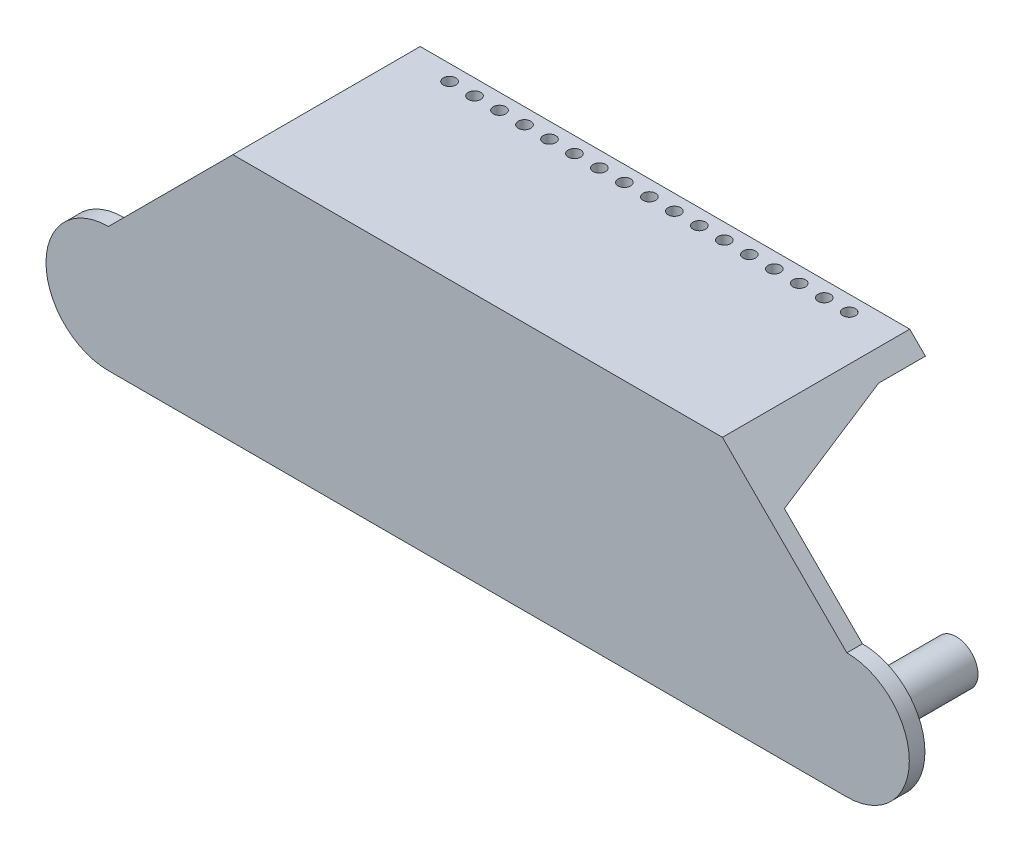
SolidWorks part; units mm, degrees
ref_plane "Спереди" through (0, 0, 0) normal (0, 0, 1) x (1, 0, 0)
ref_plane "Сверху" through (0, 0, 0) normal (0, 1, 0) x (1, 0, 0)
ref_plane "Справа" through (0, 0, 0) normal (1, 0, 0) x (0, 0, -1)
other "Configuration Table"
sketch "Эскиз1" plane through (0, 0, 0) normal (0, 0, 1) x (1, 0, 0)
  line L0 (-118.25, 0) -> (118.25, 0) construction
  line L1 (-118.25, -20) -> (118.25, -20)
  line L3 (-118.25, 20) -> (118.25, 20)
  line L5 (-118.25, -20) -> (118.25, 20) construction
  line L6 (-118.25, 20) -> (118.25, -20) construction
  arc A0 (-118.25, 20) -> (-118.25, -20) centre (-118.25, 0) ccw
  arc A1 (118.25, -20) -> (118.25, 20) centre (118.25, 0) ccw
  point P0 (0, 0)
  dimension "D3" = 20
  dimension "D1" = 236.5
  dimension "D2" = 40
extrude "Бобышка-Вытянуть1" add sketch "Эскиз1" along normal blind 5
sketch "Эскиз2" plane through (0, 0, 0) normal (0, 0, -1) x (-1, 0, 0)
  line L0 (-138.25, 0) -> (138.25, 0) construction
  line L1 (-118.25, 20) -> (-118.25, -20) construction
  line L2 (118.25, -20) -> (-118.25, -20) construction
  line L3 (118.25, 20) -> (118.25, -20) construction
  arc A0 (-118.25, 20) -> (-118.25, -20) centre (-118.25, 0) ccw construction
  arc A1 (118.25, -20) -> (118.25, 20) centre (118.25, 0) ccw construction
  circle A2 centre (-118.25, 0) radius 7
  circle A3 centre (118.25, 0) radius 7
  dimension "D1" = 14
extrude "Бобышка-Вытянуть2" add sketch "Эскиз2" along normal blind 30
sketch "Эскиз3" plane through (0, 0, 5) normal (0, 0, 1) x (1, 0, 0)
  line L0 (-138.25, 0) -> (138.25, 0) construction
  line L1 (-118.25, 20) -> (-118.25, -20) construction
  line L2 (118.25, 20) -> (118.25, -20) construction
  line L3 (-118.25, 20) -> (-78.4, 59.85)
  line L6 (78.4, 59.85) -> (-78.4, 59.85)
  line L8 (118.5, 0) -> (-118.25, 60.1) construction
  line L9 (118.25, 60.1) -> (-118.5, 0.0005) construction
  line L10 (118.25, 20) -> (-118.25, 20) construction
  line L11 (118.25, 20) -> (78.4, 59.85)
  line L12 (-118.25, 20) -> (118.25, 20)
  line L13 (-118.25, 60.1) -> (-118.25, 20) construction
  line L14 (-118.25, 60.1) -> (118.25, 60.1) construction
  line L15 (118.25, 60.1) -> (118.25, 20) construction
  arc A0 (-118.25, 20) -> (-118.25, -20) centre (-118.25, 0) ccw construction
  arc A1 (118.25, -20) -> (118.25, 20) centre (118.25, 0) ccw construction
  point P19 (-0.0005, 30.0819)
  dimension "D1" = 60.1
  dimension "D2" = 45
  dimension "D3" = 45
  dimension "D4" = 156.8
extrude "Бобышка-Вытянуть3" add sketch "Эскиз3" against normal blind 5
sketch "Эскиз4" plane through (0, 0, 0) normal (0, 0, -1) x (-1, 0, 0)
  line L0 (-124.0235, 54.85) -> (128.967, 54.85) construction
  line L1 (-78.4, 59.85) -> (78.4, 59.85) construction
  line L2 (-78.4, 59.85) -> (-83.4, 54.85)
  line L3 (-118.25, 20) -> (-78.4, 59.85) construction
  line L4 (-83.4, 54.85) -> (83.4, 54.85)
  line L5 (78.4, 59.85) -> (118.25, 20) construction
  line L6 (83.4, 54.85) -> (78.4, 59.85)
  line L7 (78.4, 59.85) -> (-78.4, 59.85)
  dimension "D1" = 5
extrude "Бобышка-Вытянуть4" add sketch "Эскиз4" along normal blind 55 contours L7 L2 L4 L6
sketch "Эскиз5" plane through (0, 59.85, 0) normal (0, 1, 0) x (1, 0, 0)
  line L0 (-78.4, 50) -> (78.4, 50) construction
  line L1 (-78.4, 55) -> (-78.4, -5) construction
  line L2 (78.4, 55) -> (78.4, -5) construction
  line L3 (78.4, -5) -> (-78.4, -5) construction
  line L4 (0, 55) -> (0, -5) construction
  line L5 (-78.4, 55) -> (78.4, 55) construction
  line L6 (0, 50) -> (8, 50) construction
  line L7 (0, 50) -> (-8, 50) construction
  circle A0 centre (0, 50) radius 2
  circle A1 centre (8, 50) radius 2
  circle A2 centre (16, 50) radius 2
  circle A3 centre (24, 50) radius 2
  circle A4 centre (32, 50) radius 2
  circle A5 centre (40, 50) radius 2
  circle A6 centre (48, 50) radius 2
  circle A7 centre (56, 50) radius 2
  circle A8 centre (64, 50) radius 2
  circle A9 centre (-8, 50) radius 2
  circle A10 centre (-16, 50) radius 2
  circle A11 centre (-24, 50) radius 2
  circle A12 centre (-32, 50) radius 2
  circle A13 centre (-40, 50) radius 2
  circle A14 centre (-48, 50) radius 2
  circle A15 centre (-56, 50) radius 2
  circle A16 centre (-64, 50) radius 2
  dimension "D2" = 4
  dimension "D1" = 55
  dimension "D3" = 9
  dimension "D4" = 8
  dimension "D6" = 8
  dimension "D5" = 9
extrude "Вырез-Вытянуть1" cut sketch "Эскиз5" against normal through all
sketch "Эскиз7" plane through (0, 0, 0) normal (0, 0, -1) x (-1, 0, 0)
  line L0 (-58.1883, 72.9906) -> (-123.7731, 7.4058) construction
  line L1 (-118.25, 20) -> (-83.4, 54.85) construction
  line L2 (-118.25, 20) -> (-111.1789, 20)
  line L3 (-111.1789, 20) -> (-76.0484, 55.1305)
  line L4 (-76.0484, 55.1305) -> (-83.4, 54.85)
  line L5 (-83.4, 54.85) -> (-118.25, 20)
  line L6 (50.1459, 81.033) -> (156.7192, -25.5402) construction
  line L7 (83.4, 54.85) -> (118.25, 20) construction
  line L8 (83.4, 54.85) -> (76.3289, 54.85)
  line L9 (76.3289, 54.85) -> (111.1789, 20)
  line L10 (111.1789, 20) -> (118.25, 20)
  line L11 (118.25, 20) -> (83.4, 54.85)
  arc A0 (-118.25, 20) -> (-118.25, -20) centre (-118.25, 0) ccw construction
  dimension "D1" = 5
  dimension "D2" = 5
extrude "Бобышка-Вытянуть5" add sketch "Эскиз7" along normal blind 40
sketch "Эскиз10" plane through (0, 0, 0) normal (1, 0, 0) x (0, 0, -1)
  line L1 (0, 50) -> (0, -50) construction
  line L2 (40, 20) -> (0, 20) construction
  line L3 (0, 20) -> (40, 20)
  line L4 (40, 20) -> (40, 54.85)
  line L5 (0, 20) -> (0, 45)
  line L6 (0, 45) -> (40, 54.85)
  dimension "D1" = 25
extrude "Вырез-Вытянуть2" cut sketch "Эскиз10" against normal through all both and the other way through all
